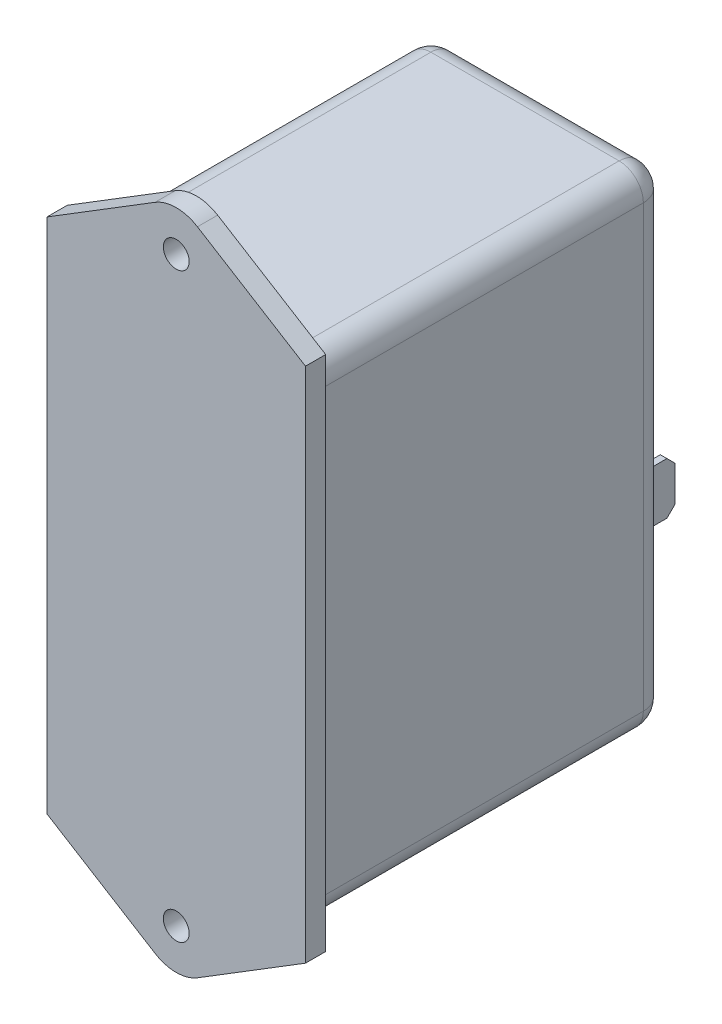
SolidWorks part; units mm, degrees
ref_plane "Front" through (0, 0, 0) normal (0, 0, 1) x (1, 0, 0)
ref_plane "Top" through (0, 0, 0) normal (0, 1, 0) x (1, 0, 0)
ref_plane "Right" through (0, 0, 0) normal (1, 0, 0) x (0, 0, -1)
sketch "Sketch1" plane through (0, 0, 0) normal (0, 0, 1) x (1, 0, 0)
  line L1 (-14.65, -30.25) -> (14.65, -30.25)
  line L2 (-14.65, -30.25) -> (-14.65, 30.25)
  line L3 (-14.65, 30.25) -> (14.65, 30.25)
  line L4 (14.65, -30.25) -> (14.65, 30.25)
  line L5 (-14.65, -30.25) -> (14.65, 30.25) construction
  line L6 (-14.65, 30.25) -> (14.65, -30.25) construction
  point P0 (0, 0)
  dimension "D1" = 29.3
  dimension "D2" = 60.5
extrude "Boss-Extrude1" add sketch "Sketch1" along normal blind 43.67
sketch "Sketch2" plane through (0, 0, 43.67) normal (0, 0, 1) x (1, 0, 0)
  line L0 (-16, 32) -> (-2.6262, 40.2548)
  line L1 (-16, -32) -> (16, -32) construction
  line L2 (-16, -32) -> (-16, 32)
  line L3 (-16, 32) -> (16, 32) construction
  line L4 (16, -32) -> (16, 32)
  line L5 (-16, -32) -> (16, 32) construction
  line L6 (-16, 32) -> (16, -32) construction
  line L7 (2.6262, 40.2548) -> (16, 32)
  line L8 (0, 36) -> (0, 32) construction
  line L9 (0, 0) -> (-16, 0) construction
  line L10 (0, -36) -> (0, -32) construction
  line L11 (-16, -32) -> (-2.6262, -40.2548)
  line L12 (2.6262, -40.2548) -> (16, -32)
  circle A0 centre (0, 36) radius 5 construction
  arc A1 (-2.6262, 40.2548) -> (2.6262, 40.2548) centre (0, 36) cw
  circle A2 centre (0, 36) radius 1.6
  circle A3 centre (0, -36) radius 5 construction
  circle A4 centre (0, -36) radius 1.6
  arc A5 (-2.6262, -40.2548) -> (2.6262, -40.2548) centre (0, -36) ccw
  point P0 (0, 0)
  point P14 (0, -41)
  point P21 (0, 41)
  dimension "D3" = 3.2
  dimension "D4" = 72
  dimension "D1" = 32
  dimension "D2" = 64
  dimension "D5" = 82
extrude "Boss-Extrude2" add sketch "Sketch2" along normal blind 2.5
fillet "Fillet1" radius 3 8 edges at (0, 30.25, 0) (-14.65, 0, 0) (0, -30.25, 0) (14.65, 0, 0) (-14.65, -30.25, 21.835) (14.65, -30.25, 21.835) (-14.65, 30.25, 21.835) (14.65, 30.25, 21.835)
sketch "Sketch3" plane through (0, 0, 0) normal (0, 0, -1) x (-1, 0, 0)
  line L0 (0, 0) -> (0, -13.75) construction
  line L1 (-10.5, -20.25) -> (10.5, -20.25)
  line L2 (-10.5, -20.25) -> (-10.5, -7.25)
  line L3 (-10.5, -7.25) -> (10.5, -7.25)
  line L4 (10.5, -20.25) -> (10.5, -7.25)
  line L5 (-10.5, -20.25) -> (10.5, -7.25) construction
  line L6 (-10.5, -7.25) -> (10.5, -20.25) construction
  line L7 (11.65, -30.25) -> (-11.65, -30.25) construction
  point P0 (0, -13.75)
  dimension "D1" = 21
  dimension "D2" = 13
  dimension "D3" = 10
extrude "Boss-Extrude3" add sketch "Sketch3" along normal blind 2
sketch "Sketch4" plane through (0, 0, -2) normal (0, 0, -1) x (-1, 0, 0)
  line L0 (0, -7.25) -> (0, -20.25) construction
  line L1 (-4.9, -16.95) -> (-5.72, -16.95)
  line L2 (-4.9, -16.95) -> (-4.9, -10.55)
  line L3 (-4.9, -10.55) -> (-5.72, -10.55)
  line L4 (-5.72, -16.95) -> (-5.72, -10.55)
  line L5 (-4.9, -16.95) -> (-5.72, -10.55) construction
  line L6 (-4.9, -10.55) -> (-5.72, -16.95) construction
  line L7 (10.5, -7.25) -> (-10.5, -7.25) construction
  line L8 (-10.5, -20.25) -> (10.5, -20.25) construction
  line L9 (-5.31, -13.75) -> (0, -13.75) construction
  line L10 (4.9, -10.55) -> (5.72, -10.55)
  line L11 (5.72, -16.95) -> (5.72, -10.55)
  line L12 (4.9, -16.95) -> (5.72, -16.95)
  line L13 (4.9, -16.95) -> (4.9, -10.55)
  point P0 (-5.31, -13.75)
  point P17 (0, -15.4774)
  point P18 (0, -13.75)
  dimension "D1" = 6.4
  dimension "D2" = 0.82
  dimension "D3" = 9.8
extrude "Boss-Extrude4" add sketch "Sketch4" along normal blind 7.85
sketch "Sketch5" plane through (0, 0, 0) normal (0, 0, -1) x (-1, 0, 0)
  line L0 (0, -25.46) -> (0, 0) construction
  line L1 (-3.2, -25.87) -> (3.2, -25.87)
  line L2 (-3.2, -25.87) -> (-3.2, -25.05)
  line L3 (-3.2, -25.05) -> (3.2, -25.05)
  line L4 (3.2, -25.87) -> (3.2, -25.05)
  line L5 (-3.2, -25.87) -> (3.2, -25.05) construction
  line L6 (-3.2, -25.05) -> (3.2, -25.87) construction
  line L9 (-10.5, -20.25) -> (10.5, -20.25) construction
  point P0 (0, -25.46)
  dimension "D1" = 6.4
  dimension "D2" = 0.82
  dimension "D3" = 4.8
extrude "Boss-Extrude5" add sketch "Sketch5" along normal up to surface (9.85 mm away) up to face at (5.31, -13.75, -9.85)
chamfer "Chamfer1" distance 1 angle 45 6 edges at (3.2, -25.46, -9.85) (5.31, -10.55, -9.85) (-5.31, -10.55, -9.85) (-5.31, -16.95, -9.85) (5.31, -16.95, -9.85) (-3.2, -25.46, -9.85)
